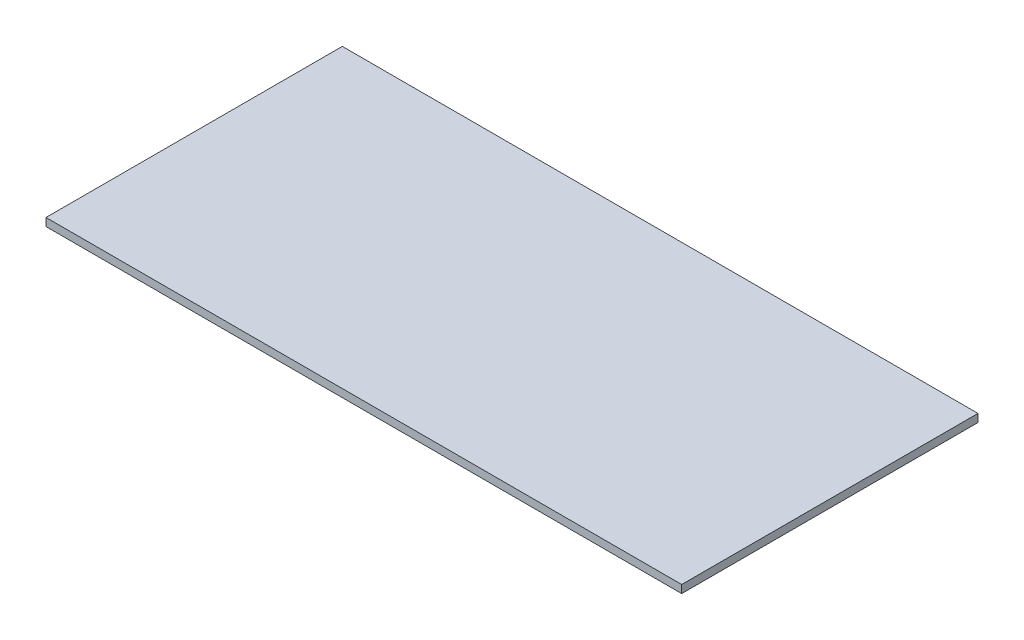
SolidWorks part; units mm, degrees
ref_plane "Front Plane" through (0, 0, 0) normal (0, 0, 1) x (1, 0, 0)
ref_plane "Top Plane" through (0, 0, 0) normal (0, 1, 0) x (1, 0, 0)
ref_plane "Right Plane" through (0, 0, 0) normal (1, 0, 0) x (0, 0, -1)
sketch "Sketch1" plane through (0, 0, 0) normal (0, 1, 0) x (1, 0, 0)
  line L1 (-16.09, -7.5) -> (16.09, -7.5)
  line L2 (-16.09, -7.5) -> (-16.09, 7.5)
  line L3 (-16.09, 7.5) -> (16.09, 7.5)
  line L4 (16.09, -7.5) -> (16.09, 7.5)
  line L5 (-16.09, -7.5) -> (16.09, 7.5) construction
  line L6 (-16.09, 7.5) -> (16.09, -7.5) construction
  point P0 (0, 0)
  dimension "D1" = 32.18
  dimension "D2" = 15
extrude "Boss-Extrude1" add sketch "Sketch1" along normal blind 0.4
